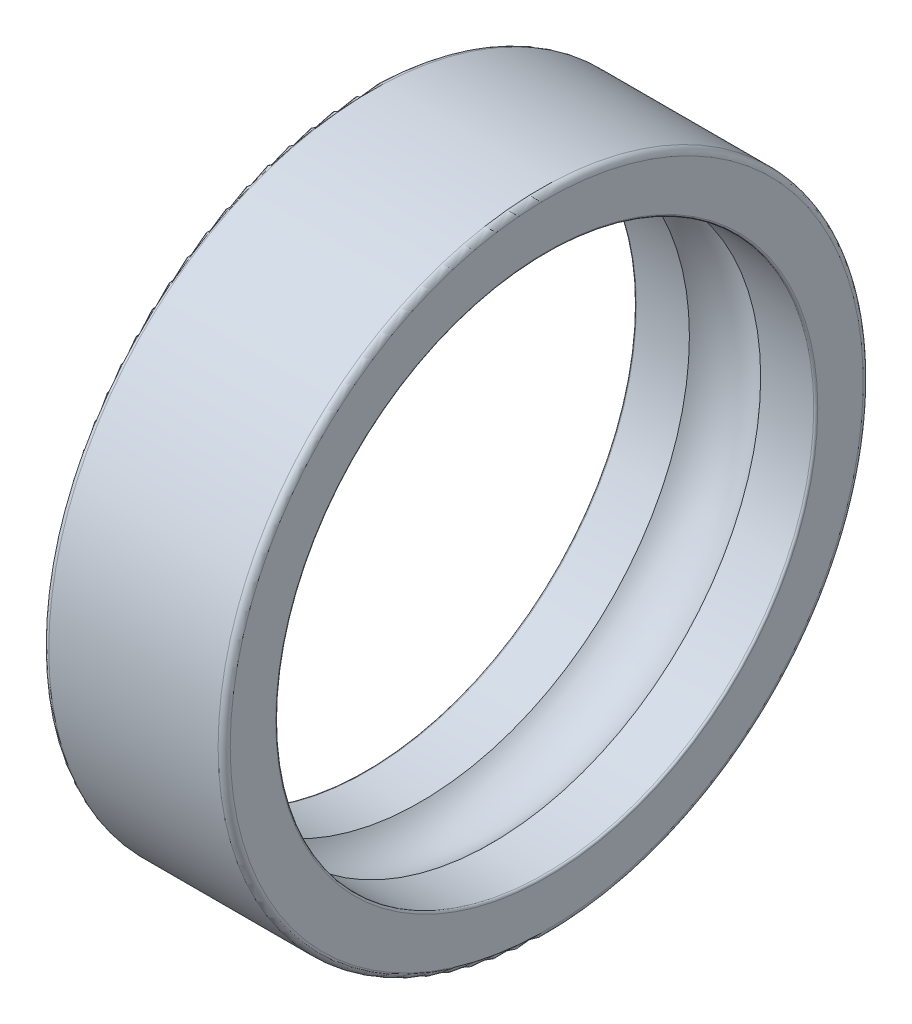
SolidWorks part; units mm, degrees
ref_plane "Plan de face" through (0, 0, 0) normal (0, 0, 1) x (1, 0, 0)
ref_plane "Plan de dessus" through (0, 0, 0) normal (0, 1, 0) x (1, 0, 0)
ref_plane "Plan de droite" through (0, 0, 0) normal (1, 0, 0) x (0, 0, -1)
ref_plane "Plan1" through (0, 0, 0) normal (0, 0, 1) x (1, 0, 0)
sketch "Esquisse1" plane through (0, 0, 0) normal (0, 0, 1) x (1, 0, 0)
  line L0 (0, 15.7) -> (0, 13.445)
  line L1 (0.1, 13.345) -> (2.7322, 13.345)
  line L2 (6.2678, 13.345) -> (8.9, 13.345)
  line L3 (9, 13.445) -> (9, 15.7)
  line L4 (8.7, 16) -> (0.3, 16)
  line L5 (50, 0) -> (-50, 0) construction
  arc A0 (0, 13.445) -> (0.1, 13.345) centre (0.1, 13.445) ccw
  arc A1 (2.7322, 13.345) -> (6.2678, 13.345) centre (4.5, 11.75) cw
  arc A2 (8.9, 13.345) -> (9, 13.445) centre (8.9, 13.445) ccw
  arc A3 (9, 15.7) -> (8.7, 16) centre (8.7, 15.7) ccw
  arc A4 (0.3, 16) -> (0, 15.7) centre (0.3, 15.7) ccw
revolve "Révolution1" add sketch "Esquisse1" angle 360 about L5
